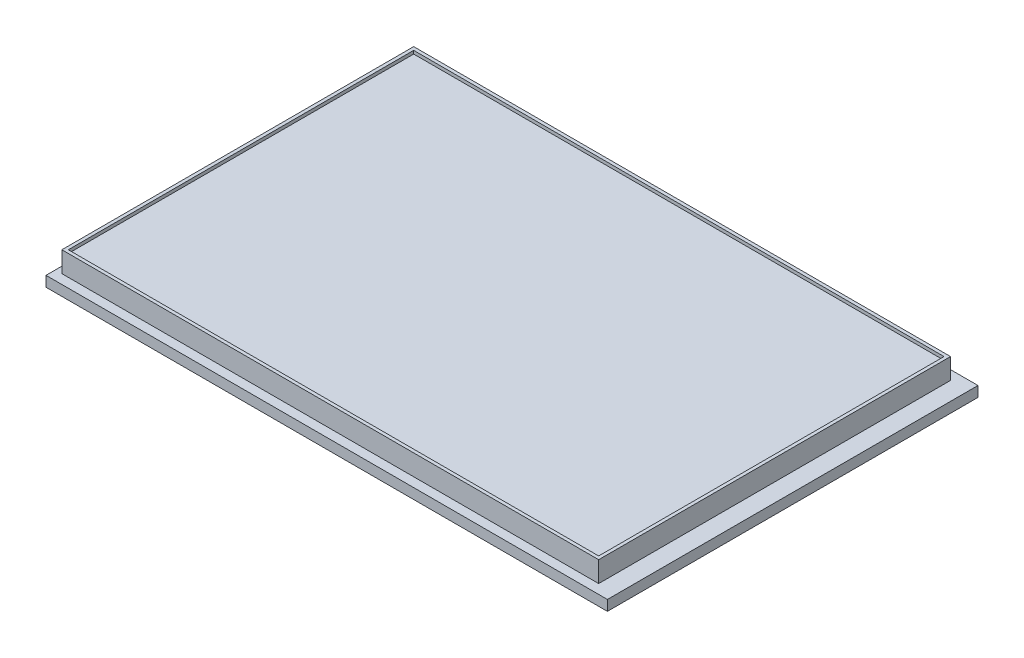
SolidWorks part; units mm, degrees
ref_plane "Front Plane" through (0, 0, 0) normal (0, 0, 1) x (1, 0, 0)
ref_plane "Top Plane" through (0, 0, 0) normal (0, 1, 0) x (1, 0, 0)
ref_plane "Right Plane" through (0, 0, 0) normal (1, 0, 0) x (0, 0, -1)
sketch "Sketch1" plane through (0, 0, 0) normal (0, 1, 0) x (1, 0, 0)
  line L1 (-43.4, 28.65) -> (43.4, 28.65)
  line L2 (-43.4, 28.65) -> (-43.4, -28.65)
  line L3 (-43.4, -28.65) -> (43.4, -28.65)
  line L4 (43.4, 28.65) -> (43.4, -28.65)
  line L5 (-43.4, 28.65) -> (43.4, -28.65) construction
  line L6 (-43.4, -28.65) -> (43.4, 28.65) construction
  point P0 (0, 0)
  dimension "D1" = 57.3
  dimension "D2" = 86.8
extrude "Boss-Extrude1" add sketch "Sketch1" along normal blind 1.6
sketch "Sketch2" plane through (0, 1.6, 0) normal (0, 1, 0) x (1, 0, 0)
  line L0 (-43.4, 0) -> (43.4, 0) construction
  line L6 (-42.4, 27.2) -> (40.6, 27.2)
  line L7 (-43.4, 28.65) -> (-43.4, -28.65) construction
  line L8 (43.4, -28.65) -> (43.4, 28.65) construction
  line L9 (-42.4, 27.2) -> (-42.4, -27.2)
  line L10 (-42.4, -27.2) -> (40.6, -27.2)
  line L11 (40.6, 27.2) -> (40.6, -27.2)
  line L12 (-42.4, 27.2) -> (40.6, -27.2) construction
  line L13 (-42.4, -27.2) -> (40.6, 27.2) construction
  point P0 (-15.3171, 0)
  point P1 (-0.9, 0)
  dimension "D1" = 54.4
  dimension "D2" = 83
  dimension "D3" = 2.8
extrude "Boss-Extrude2" add sketch "Sketch2" along normal blind 3.2
sketch "Sketch3" plane through (0, 4.8, 0) normal (0, 1, 0) x (1, 0, 0)
  line L0 (40.6, 27.2) -> (-42.4, 27.2) construction
  line L1 (-41.9, 26.7) -> (40.1, 26.7)
  line L2 (-41.9, 26.7) -> (-41.9, -26.7)
  line L3 (-41.9, -26.7) -> (40.1, -26.7)
  line L4 (40.1, 26.7) -> (40.1, -26.7)
  line L5 (-41.9, 26.7) -> (40.1, -26.7) construction
  line L6 (-41.9, -26.7) -> (40.1, 26.7) construction
  line L7 (-42.4, -27.2) -> (40.6, -27.2) construction
  line L8 (-42.4, 27.2) -> (-42.4, -27.2) construction
  line L9 (40.6, -27.2) -> (40.6, 27.2) construction
  point P0 (-0.9, 0)
  dimension "D1" = 0.5
  dimension "D2" = 0.5
  dimension "D3" = 0.5
  dimension "D4" = 0.5
extrude "Cut-Extrude1" cut sketch "Sketch3" against normal blind 0.5
sketch "Sketch5" plane through (0, 4.3, 0) normal (0, 1, 0) x (1, 0, 0)
  line L0 (-376.8357, 132.672) -> (-56.8357, 132.672) construction
